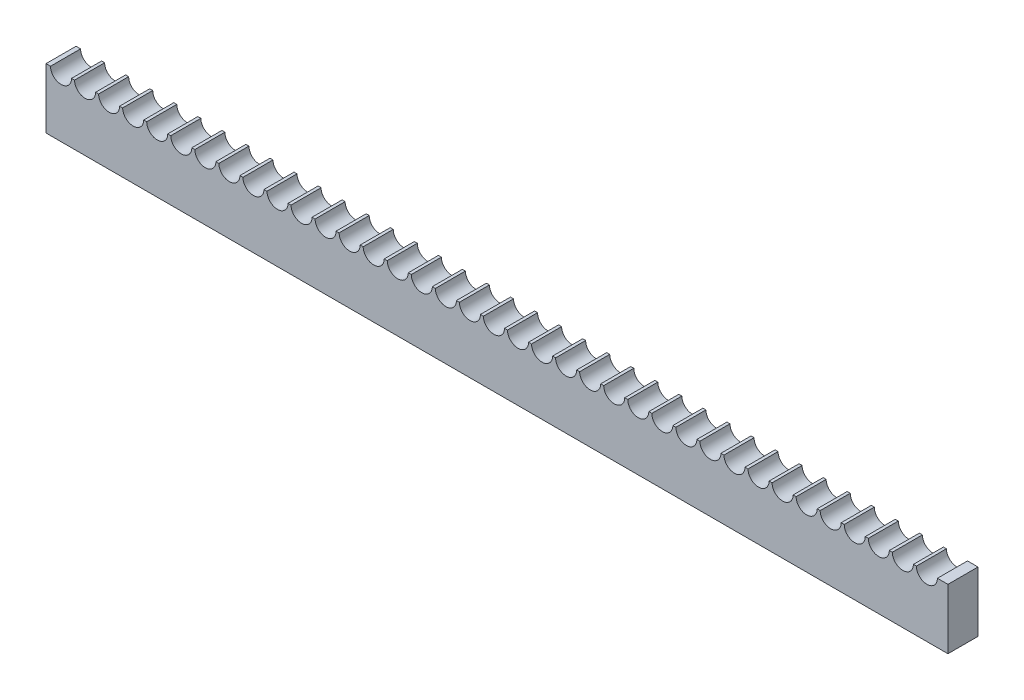
SolidWorks part; units mm, degrees
material "Copper"
ref_plane "Front Plane" through (0, 0, 0) normal (0, 0, 1) x (1, 0, 0)
ref_plane "Top Plane" through (0, 0, 0) normal (0, 1, 0) x (1, 0, 0)
ref_plane "Right Plane" through (0, 0, 0) normal (1, 0, 0) x (0, 0, -1)
sketch "Sketch1" plane through (0, 0, 0) normal (0, 0, 1) x (1, 0, 0)
  line L1 (-190.5, 25.4) -> (190.5, 25.4)
  line L2 (-190.5, 25.4) -> (-190.5, 0)
  line L3 (-190.5, 0) -> (190.5, 0)
  line L4 (190.5, 25.4) -> (190.5, 0)
  dimension "D1" = 25.4
  dimension "D2" = 381
extrude "Boss-Extrude1" add sketch "Sketch1" along normal blind 12.7
sketch "Sketch2" plane through (0, 0, 12.7) normal (0, 0, 1) x (1, 0, 0)
  line L0 (190.5, 25.4) -> (-190.5, 25.4) construction
  line L1 (-190.5, 25.4) -> (-190.5, 0) construction
  circle A0 centre (-184.15, 25.4) radius 4.445
  dimension "D1" = 8.89
  dimension "D2" = 6.35
extrude "Cut-Extrude1" cut sketch "Sketch2" against normal up to next
pattern_linear "LPattern1" count 37 spacing 10.16 along (1, 0, 0) of "Cut-Extrude1"
